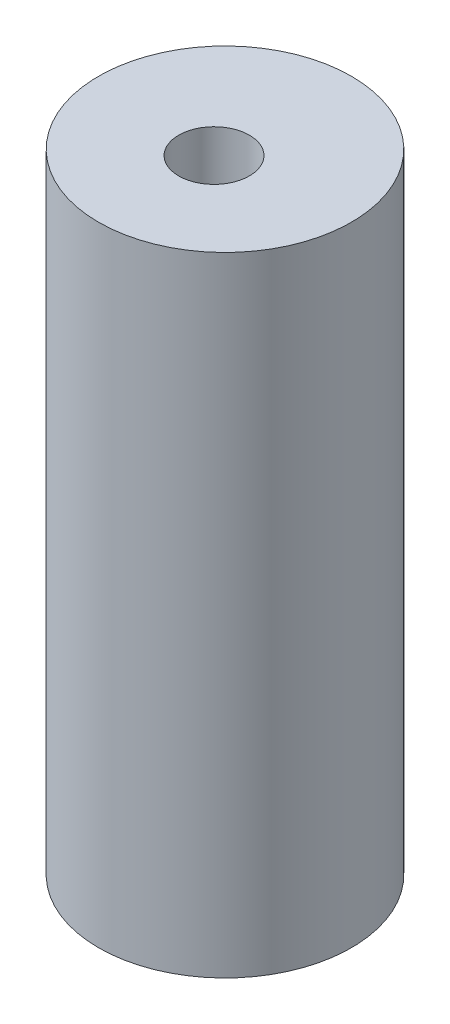
SolidWorks part; units mm, degrees
ref_plane "Ebene vorne" through (0, 0, 0) normal (0, 0, 1) x (1, 0, 0)
ref_plane "Ebene oben" through (0, 0, 0) normal (0, 1, 0) x (1, 0, 0)
ref_plane "Ebene rechts" through (0, 0, 0) normal (1, 0, 0) x (0, 0, -1)
sketch "Skizze1" plane through (0, 0, 0) normal (0, 1, 0) x (1, 0, 0)
  circle A0 centre (0, 0) radius 8.05
  dimension "D1" = 16.1
extrude "Aufsatz-Linear austragen1" add sketch "Skizze1" along normal blind 40
hole_wizard "Durchgangsloch für M41" positions "Skizze2" profile "Skizze4" hole size "M4" standard "DIN" end condition through all
sketch "Skizze2" plane through (0, 40, 0) normal (0, 1, 0) x (1, 0, 0)
  point P0 (0, -0.6985)
sketch "Skizze4" plane through (0, 40, 0.6985) normal (1, 0, 0) x (0, 0, 1)
  line L0 (0, 0) -> (0, 40)
  line L1 (0, 40) -> (2.25, 40)
  line L2 (2.25, 40) -> (2.25, 0)
  line L5 (2.25, 0) -> (0, 0)
  line L11 (0, -6.35) -> (0, 107.95) construction
  dimension "Bohrerdurchmesser" = 4.5
  dimension "Bohrungstiefe" = 40
